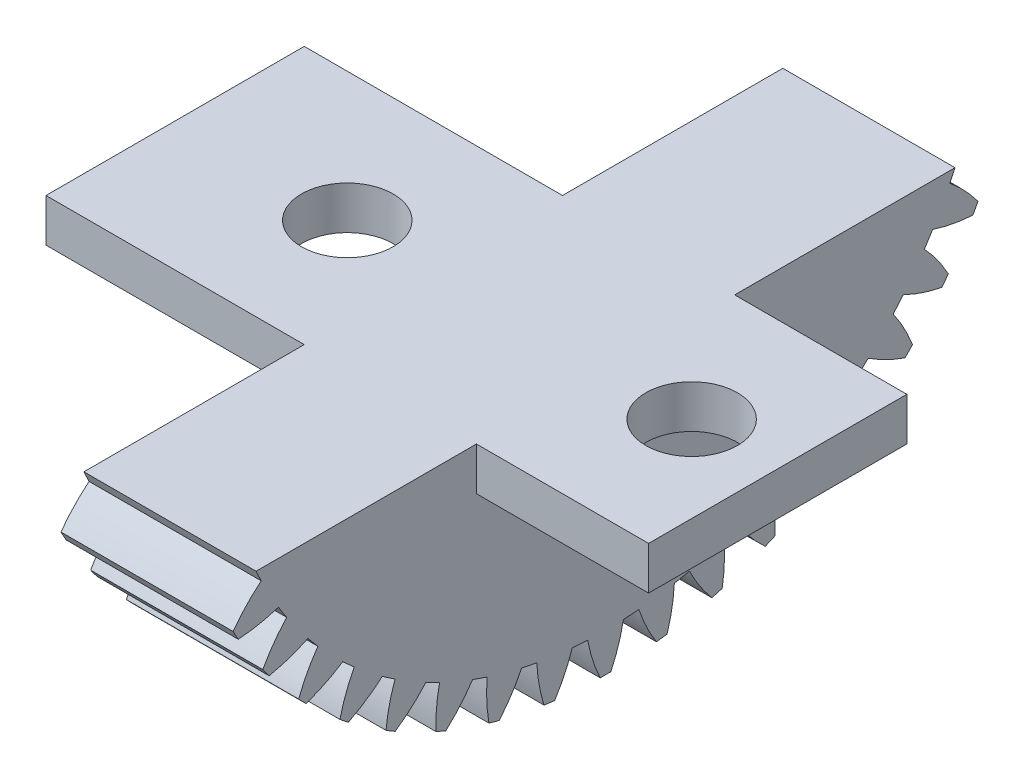
SolidWorks part; units mm, degrees
material "ABS"
ref_plane "Plane1" through (0, 0, 0) normal (0, 0, 1) x (1, 0, 0)
ref_plane "Plane2" through (0, 0, 0) normal (0, 1, 0) x (1, 0, 0)
ref_plane "Plane3" through (0, 0, 0) normal (1, 0, 0) x (0, 0, -1)
other "Configuration Table"
sketch "HoldingSke" plane through (0, 0, 0) normal (0, 1, 0) x (1, 0, 0)
  line L0 (0, 0) -> (346.4552, -371.5277)
  line L1 (-15, 0) -> (100, 0) construction
  line L2 (0, 0) -> (-2.1039, 2.3779)
  line L3 (0, 0) -> (-11.863, 4.5341)
  line L4 (0, 0) -> (5.8897, 6.316)
  line L5 (0, 0) -> (-47.5972, -17.7524)
  line L6 (0, 0) -> (-10.5278, -7.1032)
  line L7 (-2.1039, 2.3779) -> (8.8308, 51.9871)
  line L8 (-76.2, 54.61) -> (-72.771, 54.61)
  line L9 (-71.009, 38.7566) -> (-53.1078, 45.2721)
  line L10 (-76.2, 71.12) -> (104.1128, 71.12)
  line L11 (0, 0) -> (-12.7, 0)
  line L12 (-76.2, 101.6) -> (-76.1492, 101.6)
  line L13 (24.9733, 27.94) -> (52.9518, 28.4284)
  line L14 (24.9733, 27.94) -> (25.0241, 27.9398)
  line L15 (24.9733, 27.94) -> (100.4021, 29.52)
  circle A0 centre (0, 0) radius 1.5875
  circle A1 centre (0, 0) radius 28.2702
  circle A2 centre (0, 0) radius 38.1
  circle A3 centre (0, 0) radius 1.5875
  dimension "MHD" = 56.5404
  dimension "Hub_dia" = 76.2
  dimension "Bore" = 3.175
  dimension "MBD" = 3.175
  dimension "Num_teeth" = 47
  dimension "Pitch" = 508
  dimension "Overall_len" = 50.8
  dimension "Show_teeth" = 47
  dimension "Thickness" = 12.7
  dimension "OAL" = 50.8001
  dimension "T_dim" = 3.429
  dimension "Ap" = 20
  dimension "H" = 19.05
  dimension "Pitch_radius" = 180.3128
  dimension "Width" = 12.7
  dimension "Backlash" = 0.0508
  dimension "Addendum_fac" = 1
  dimension "Dedendum_fac" = 1.2
  dimension "Clearance_fac" = 0.2
  dimension "Dedendum_add" = 0.0508
sketch "BasProSke" plane through (0, 0, 0) normal (0, 1, 0) x (1, 0, 0)
  line L0 (-10, 0) -> (60, 0) construction
  line L1 (0, 0) -> (0, 31.115)
  line L2 (0, 0) -> (12.7, 0)
  line L3 (12.7, 0) -> (12.7, 31.115)
  line L4 (12.7, 31.115) -> (0, 31.115)
  dimension "Thickness" = 12.7
  dimension "Diameter" = 62.23
revolve "Base-Revolve" add sketch "BasProSke" angle 360 about L0
sketch "TooCutSke" plane through (0, 0, 0) normal (1, 0, 0) x (0, 0, -1)
  line L1 (0, 0) -> (0, 107) construction
  line L2 (0, 0) -> (-1.0862, 29.8252) construction
  line L3 (0, 0) -> (-3.985, 59.5291) construction
  line L4 (-1.0862, 29.8252) -> (-1.9925, 29.7646) construction
  arc A0 (0.5672, 28.2645) -> (-0.5672, 28.2645) centre (0, 0) ccw
  arc A1 (1.6975, 31.0941) -> (-1.6975, 31.0941) centre (0, 0) ccw
  circle A2 centre (0, 0) radius 29.845 construction
  circle A3 centre (0, 0) radius 28.0451 construction
  arc A4 (-0.5672, 28.2645) -> (-1.6975, 31.0941) centre (-12.128, 25.2872) ccw
  arc A5 (1.6975, 31.0941) -> (0.5672, 28.2645) centre (12.128, 25.2872) ccw
  dimension "Root_dia" = 56.5404
  dimension "Overcut_dia" = 62.2808
  dimension "Pitch_dia" = 59.69
  dimension "Base_dia" = 56.0903
  dimension "Flank_rad" = 11.938
  dimension "Half_ang" = 3.83
  dimension "Half_CT" = 0.9084
extrude "ToothCut" cut sketch "TooCutSke" along normal through all
fillet "Breaks" [suppressed] radius 0.0254
fillet "RootFillets" [suppressed] radius 0.3048
pattern_circular "TeethCuts" count 47 every 7.66 about axis through (-10, 0, 0) along (1, 0, 0) of "ToothCut", "RootFillets", "Breaks"
sketch "HubNeaOneSke" plane through (0, 0, 0) normal (-1, 0, 0) x (0, 0, 1)
  circle A0 centre (0, 0) radius 28.2702
  dimension "Diameter" = 56.5404
extrude "HubNearOne" [suppressed] add sketch "HubNeaOneSke" along normal blind 38.1001
sketch "HubNeaBotSke" plane through (0, 0, 0) normal (-1, 0, 0) x (0, 0, 1)
  circle A0 centre (0, 0) radius 28.2702
  dimension "Diameter" = 56.5404
extrude "HubNearBoth" [suppressed] add sketch "HubNeaBotSke" along normal blind 19.05
ref_plane "FarPln" through (12.7, 0, 0) normal (1, 0, 0) x (0, 0, -1)
sketch "HubFarSke" plane through (12.7, 0, 0) normal (1, 0, 0) x (0, 0, -1)
  circle A0 centre (0, 0) radius 28.2702
  dimension "Diameter" = 56.5404
extrude "HubFar" [suppressed] add sketch "HubFarSke" along normal blind 19.05
sketch "BorSke" plane through (0, 0, 0) normal (1, 0, 0) x (0, 0, -1)
  circle A0 centre (0, 0) radius 1.5875
  dimension "Diameter" = 3.175
extrude "Bore" cut sketch "BorSke" along normal mid plane 101.6001
sketch "KeySke" plane through (0, 0, 0) normal (1, 0, 0) x (0, 0, -1)
  line L0 (-0.127, 0) -> (-0.127, 1.8415)
  line L1 (-0.127, 1.8415) -> (0.127, 1.8415)
  line L2 (0.127, 1.8415) -> (0.127, 0)
  line L3 (0, 0) -> (0, 34) construction
  line L4 (-0.127, 0) -> (0.127, 0)
  dimension "Offset" = 1.8415
  dimension "Width" = 0.254
extrude "Keyway" [suppressed] cut sketch "KeySke" along normal mid plane 101.6001
pattern_circular "Keyway2" [suppressed] count 2 every 90 about axis through (-10, 0, 0) along (1, 0, 0)
sketch "Sketch1" plane through (12.7, 0, 0) normal (1, 0, 0) x (0, 0, -1)
  line L1 (28.8687, -11.6078) -> (-28.8687, -11.6078)
  arc A1 (28.8687, -11.6078) -> (-28.8687, -11.6078) centre (0, 0) ccw
  dimension "D1" = 11.6078
extrude "Cut-Extrude2" cut sketch "Sketch1" against normal through all
sketch "Sketch2" plane through (0, 0, 0) normal (-1, 0, 0) x (0, 0, 1)
  line L0 (25.7772, -11.6078) -> (-25.7772, -11.6078) construction
  line L1 (-9.525, -11.6078) -> (9.525, -11.6078)
  line L2 (-9.525, -11.6078) -> (-9.525, -14.7828)
  line L3 (-9.525, -14.7828) -> (9.525, -14.7828)
  line L4 (9.525, -11.6078) -> (9.525, -14.7828)
  line L5 (0, -31.115) -> (0, -14.7828)
  line L7 (-9.525, -13.1953) -> (0, -13.1953) construction
  line L8 (0, -13.1953) -> (9.525, -13.1953) construction
  line L9 (0, -14.7828) -> (0, -11.6078) construction
  arc A0 (-0.3952, -31.1125) -> (0.3952, -31.1125) centre (0, 0) ccw construction
  point P6 (0, -14.7828)
  dimension "D1" = 3.175
  dimension "D2" = 19.05
extrude "Boss-Extrude1" add sketch "Sketch2" along normal blind 19.05 and the other way through all from surface at 0 contours L4 L1 L2 L3 starting at face at (0, -23.3743, 0)
sketch "Sketch4" plane through (12.7, 0, 0) normal (1, 0, 0) x (0, 0, -1)
  line L0 (-25.7772, -11.6078) -> (25.7772, -11.6078) construction
  line L1 (-9.525, -11.6078) -> (9.525, -11.6078)
  line L2 (-9.525, -11.6078) -> (-9.525, -14.7828)
  line L3 (-9.525, -14.7828) -> (9.525, -14.7828)
  line L4 (9.525, -11.6078) -> (9.525, -14.7828)
  line L5 (-9.525, -13.1953) -> (0, -13.1953) construction
  line L6 (0, -13.1953) -> (9.525, -13.1953) construction
  point P9 (0, -11.6078)
  dimension "D1" = 3.175
  dimension "D2" = 19.05
extrude "Boss-Extrude2" add sketch "Sketch4" along normal blind 12.7
hole_wizard "1/4 Clearance Hole1" positions "3DSketch1" profile "Sketch5" hole size "1/4" standard "ANSI Inch" end condition through all
sketch3d "3DSketch1"
  line L0 (25.4, -11.6078, -9.525) -> (25.4, -11.6078, 9.525) construction
  line L1 (0, -11.6078, 25.7772) -> (0, -11.6078, 9.525) construction
  line L3 (25.4, -11.6078, -9.525) -> (12.7, -11.6078, -9.525) construction
  line L4 (0, -11.6078, -9.525) -> (-19.05, -11.6078, -9.525) construction
  point P0 (19.05, -11.6078, 0)
  point P2 (-6.35, -11.6078, 0)
  dimension "D1" = 6.35
  dimension "D2" = 6.35
  dimension "D3" = 9.525
  dimension "D4" = 9.525
sketch "Sketch5" plane through (19.05, -11.6078, 0) normal (1, 0, 0) x (0, 0, 1)
  line L0 (0, 0) -> (0, 19.5072)
  line L1 (0, 19.5072) -> (3.3782, 19.5072)
  line L2 (3.3782, 19.5072) -> (3.3782, 0)
  line L5 (3.3782, 0) -> (0, 0)
  line L11 (0, -6.35) -> (0, 107.95) construction
  dimension "Thru Hole Dia." = 6.7564
  dimension "Thru Hole Depth" = 19.5072
equation "' \"Pitch@HoldingSke\" = 4"
equation "' \"Num_teeth@HoldingSke\" = 12"
equation "' \"Ap@HoldingSke\" =  20"
equation "' \"Ap@HoldingSke\" = 20"
equation "' \"Width@HoldingSke\" = 0.5"
equation "' \"Hub_dia@HoldingSke\"= 1"
equation "' \"Hub_dia@HoldingSke\" = 1"
equation "' \"Overall_len@HoldingSke\" = 1.0"
equation "' \"Bore@HoldingSke\" = 0.75"
equation "' \"T_dim@HoldingSke\" = 0.85"
equation "' \"Width@KeySke\" = 0.25"
equation "' \"Show_teeth@HoldingSke\" = 13"
equation "' \"Backlash@HoldingSke\" = 0.009"
equation "' \"Addendum_fac@HoldingSke\" = 1.0"
equation "' \"Dedendum_fac@HoldingSke\" = 1.25"
equation "' \"Dedendum_add@HoldingSke\" = 0.00005"
equation "' \"Clearance_fac@HoldingSke\" = 0.25"
equation "' \"Pitch@HoldingSke\" = 0.5"
equation "' \"Num_teeth@HoldingSke\" = 23"
equation "' \"Show_teeth@HoldingSke\" = 23"
equation "' \"Backlash@HoldingSke\" = 0.0375"
equation "\"Overcut_dia@TooCutSke\" = (\"Num_teeth@HoldingSke\" + 2 * \"Addendum_fac@HoldingSke\") / \"Pitch@HoldingSke\" + 0.002"
equation "\"Pitch_dia@TooCutSke\" = \"Num_teeth@HoldingSke\" / \"Pitch@HoldingSke\""
equation "\"Base_dia@TooCutSke\" = \"Num_teeth@HoldingSke\" / \"Pitch@HoldingSke\" * cos((\"Ap@HoldingSke\"  * 3.14159265 / 180))"
equation "\"Root_dia@TooCutSke\" = (\"Num_teeth@HoldingSke\" + 2) / \"Pitch@HoldingSke\" - 2 * (\"Addendum_fac@HoldingSke\" + \"Dedendum_fac@HoldingSke\") / \"Pitch@HoldingSke\" - \"Dedendum_add@HoldingSke\" * 2"
equation "\"Half_ang@TooCutSke\" = 180 / \"Num_teeth@HoldingSke\""
equation "\"Half_CT@TooCutSke\" = \"Num_teeth@HoldingSke\" / \"Pitch@HoldingSke\" * sin((3.14159265 / 2 / \"Num_teeth@HoldingSke\")) / 2 - 7 * \"Backlash@HoldingSke\" / 4"
equation "\"Flank_rad@TooCutSke\" = \"Num_teeth@HoldingSke\" / \"Pitch@HoldingSke\" / 5"
equation "\"Radius@RootFillets\" = \"Clearance_fac@HoldingSke\" / \"Pitch@HoldingSke\" + \"Dedendum_add@HoldingSke\""
equation "\"Break_rad@Breaks\" = 0.02 / \"Pitch@HoldingSke\""
equation "\"Thickness@HoldingSke\" = \"Width@HoldingSke\""
equation "\"OAL@HoldingSke\" = \"Thickness@HoldingSke\""
equation "\"MHD@HoldingSke\" = (\"Num_teeth@HoldingSke\" + 2) / \"Pitch@HoldingSke\" - 2 * (\"Addendum_fac@HoldingSke\" + \"Dedendum_fac@HoldingSke\")  / \"Pitch@HoldingSke\" - \"Dedendum_add@HoldingSke\" * 2"
equation "\"MBD@HoldingSke\" = (\"Num_teeth@HoldingSke\" + 2) / \"Pitch@HoldingSke\" - 2 * (\"Addendum_fac@HoldingSke\" + \"Dedendum_fac@HoldingSke\")  / \"Pitch@HoldingSke\" - \"Dedendum_add@HoldingSke\" * 2 - 0.002"
equation "\"MHD@HoldingSke\" = ((sgn( \"MHD@HoldingSke\" - \"Hub_dia@HoldingSke\" )-1)*( \"MHD@HoldingSke\" - \"Hub_dia@HoldingSke\" ))/-2+ \"Hub_dia@HoldingSke\""
equation "\"MBD@HoldingSke\" = ((sgn( \"MBD@HoldingSke\" - \"Bore@HoldingSke\" )-1)*( \"MBD@HoldingSke\" - \"Bore@HoldingSke\" ))/-2+ \"Bore@HoldingSke\""
equation "\"OAL@HoldingSke\" = ((sgn( \"OAL@HoldingSke\" - \"Overall_len@HoldingSke\" )+1)*( \"OAL@HoldingSke\" - \"Overall_len@HoldingSke\" ))/2 + \"Overall_len@HoldingSke\" + 0.000002"
equation "\"Num_teeth@TeethCuts\" = int( \"Show_teeth@HoldingSke\" ) + 1"
equation "\"Num_teeth@TeethCuts\" = ((sgn( \"Num_teeth@TeethCuts\" - \"Num_teeth@HoldingSke\" )-1)*( \"Num_teeth@TeethCuts\" - \"Num_teeth@HoldingSke\" ))/-2+ \"Num_teeth@HoldingSke\""
equation "\"Num_teeth@TeethCuts\" = ((sgn( \"Num_teeth@TeethCuts\" - 2.0)+1)*( \"Num_teeth@TeethCuts\" - 2.0))/2 +2.0"
equation "\"Angle@TeethCuts\" = 360.0 / \"Num_teeth@HoldingSke\""
equation "\"Diameter@BasProSke\" = (\"Num_teeth@HoldingSke\" + 2 * \"Addendum_fac@HoldingSke\") / \"Pitch@HoldingSke\""
equation "\"Thickness@BasProSke\"  = \"Thickness@HoldingSke\""
equation "' \"Fillet_rad@BasProSke\" =  \"Thickness@HoldingSke\" * 0.05"
equation "' \"Fillet_rad@BasProSke\" = \"Thickness@HoldingSke\" * 0.05"
equation "\"MHD@HoldingSke\" = ((sgn( \"MHD@HoldingSke\" - \"Root_dia@TooCutSke\" )-1)*( \"MHD@HoldingSke\" - \"Root_dia@TooCutSke\" ))/-2+ \"Root_dia@TooCutSke\""
equation "\"Diameter@HubNeaOneSke\" = \"MHD@HoldingSke\""
equation "\"Length@HubNearOne\" = \"OAL@HoldingSke\" - \"Thickness@BasProSke\""
equation "\"Diameter@HubNeaBotSke\" = \"MHD@HoldingSke\""
equation "\"Length@HubNearBoth\" = ( \"OAL@HoldingSke\" - \"Thickness@BasProSke\" ) / 2.0"
equation "\"Thickness@FarPln\" = \"Thickness@BasProSke\""
equation "\"Diameter@HubFarSke\" = \"MHD@HoldingSke\""
equation "\"Length@HubFar\" = ( \"OAL@HoldingSke\" - \"Thickness@BasProSke\" ) / 2.0"
equation "\"Diameter@BorSke\" = \"MBD@HoldingSke\""
equation "\"D1@Bore\" = \"OAL@HoldingSke\" * 2.0"
equation "\"D1@Keyway\" = \"OAL@HoldingSke\" * 2.0"
equation "\"Offset@KeySke\" = \"T_dim@HoldingSke\" - \"MBD@HoldingSke\" / 2.0"
